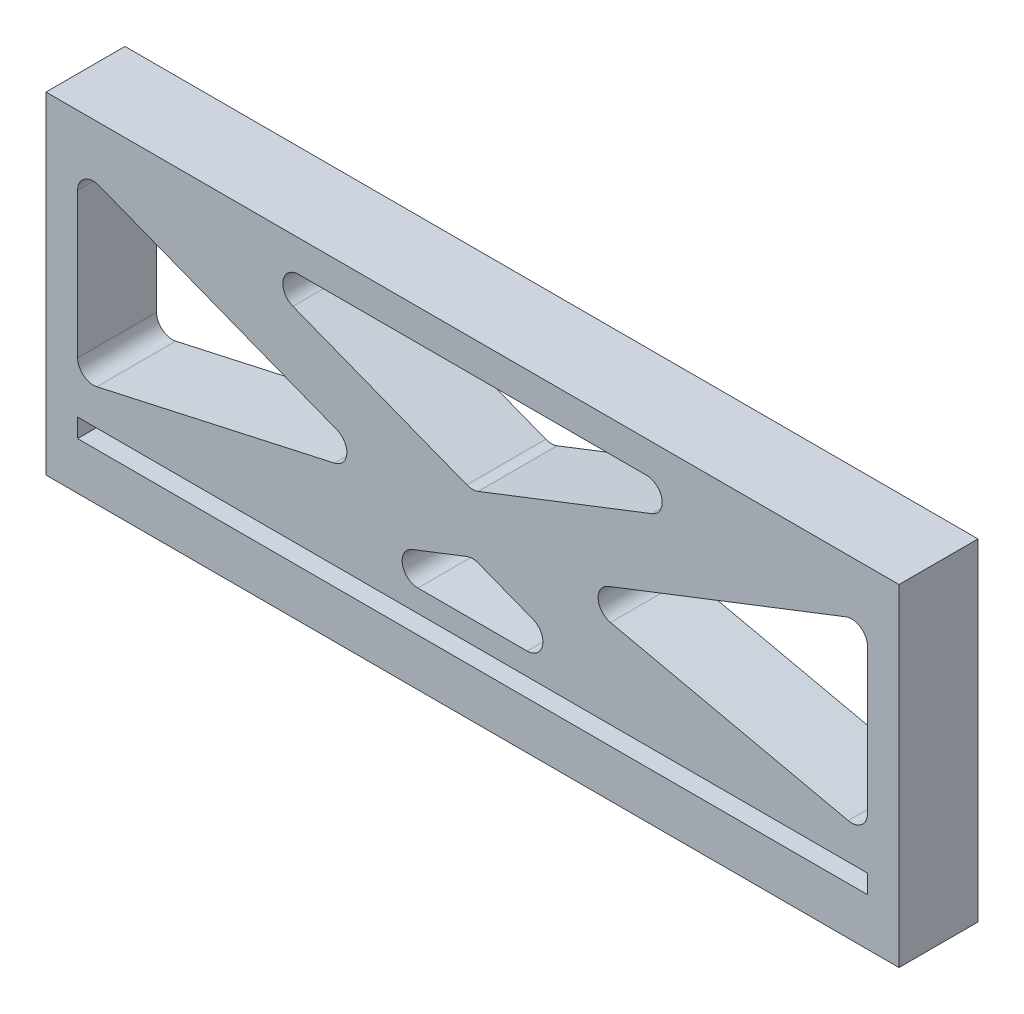
SolidWorks part; units mm, degrees
ref_plane "Front Plane" through (0, 0, 0) normal (0, 0, 1) x (1, 0, 0)
ref_plane "Top Plane" through (0, 0, 0) normal (0, 1, 0) x (1, 0, 0)
ref_plane "Right Plane" through (0, 0, 0) normal (1, 0, 0) x (0, 0, -1)
sketch "Sketch1" plane through (0, 0, 0) normal (0, 0, 1) x (1, 0, 0)
  line L0 (-20.7506, 10.795) -> (0, 2.7253)
  line L1 (-34.29, -13.335) -> (34.29, -13.335)
  line L2 (-34.29, -13.335) -> (-34.29, 13.335)
  line L3 (-34.29, 13.335) -> (34.29, 13.335)
  line L4 (34.29, -13.335) -> (34.29, 13.335)
  line L5 (-34.29, -13.335) -> (34.29, 13.335) construction
  line L6 (-34.29, 13.335) -> (34.29, -13.335) construction
  line L7 (-31.75, -9.525) -> (31.75, -9.525)
  line L8 (-31.75, -9.525) -> (-31.75, -8.025)
  line L9 (-31.75, -8.025) -> (31.75, -8.025)
  line L10 (31.75, -9.525) -> (31.75, -8.025)
  line L11 (-31.75, -9.525) -> (31.75, -8.025) construction
  line L12 (-31.75, -8.025) -> (31.75, -9.525) construction
  line L13 (0, 2.7253) -> (20.7506, 10.795)
  line L14 (20.7506, 10.795) -> (-20.7506, 10.795)
  line L15 (0, 0) -> (0, 2.7253) construction
  line L16 (-10.3753, 6.7602) -> (-11.2959, 4.3929) construction
  line L17 (10.3753, 6.7602) -> (11.2959, 4.3929) construction
  line L18 (0, 10.795) -> (0, 13.335) construction
  line L19 (-31.75, 9.6219) -> (-31.75, -5.485)
  line L20 (-31.75, -5.485) -> (-7.0079, 0)
  line L21 (-7.0079, 0) -> (-31.75, 9.6219)
  line L22 (7.0079, 0) -> (-7.0079, 0) construction
  line L23 (-19.379, 4.811) -> (-18.4584, 7.1782) construction
  line L24 (7.0079, 0) -> (31.75, 9.6219)
  line L25 (31.75, 9.6219) -> (31.75, -5.485)
  line L26 (31.75, -5.485) -> (7.0079, 0)
  line L27 (0, -1.9077) -> (-11.1582, -6.247)
  line L28 (-11.1582, -6.247) -> (11.1582, -6.247)
  line L29 (11.1582, -6.247) -> (0, -1.9077)
  line L30 (0, -1.9077) -> (0, 0) construction
  line L31 (-5.5791, -4.0774) -> (-6.2235, -2.4203) construction
  line L32 (5.5791, -4.0774) -> (6.2235, -2.4203) construction
  line L33 (0, -6.247) -> (0, -8.025) construction
  point P0 (0, 0)
  point P6 (0, -8.775)
  point P27 (0, 0)
  dimension "D1" = 3.81
  dimension "D2" = 2.54
  dimension "D3" = 68.58
  dimension "D4" = 26.67
  dimension "D5" = 1.5
  dimension "D6" = 2.54
  dimension "D7" = 2.54
  dimension "D8" = 2.54
  dimension "D9" = 1.778
extrude "Boss-Extrude1" add sketch "Sketch1" along normal blind 6.35
fillet "Fillet1" radius 1.27 12 edges at (31.75, 9.6219, 3.175) (31.75, -5.485, 3.175) (7.0079, 0, 3.175) (20.7506, 10.795, 3.175) (-20.7506, 10.795, 3.175) (0, 2.7253, 3.175) (-7.0079, 0, 3.175) (-31.75, 9.6219, 3.175) (-31.75, -5.485, 3.175) (11.1582, -6.247, 3.175) (0, -1.9077, 3.175) (-11.1582, -6.247, 3.175)
